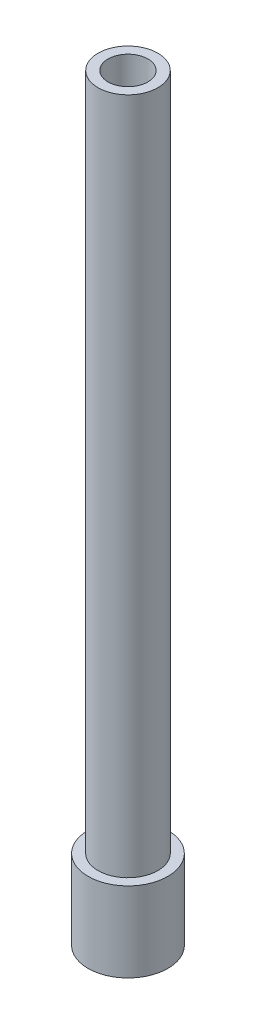
SolidWorks part; units mm, degrees
material "Copper"
ref_plane "Front Plane" through (0, 0, 0) normal (0, 0, 1) x (1, 0, 0)
ref_plane "Top Plane" through (0, 0, 0) normal (0, 1, 0) x (1, 0, 0)
ref_plane "Right Plane" through (0, 0, 0) normal (1, 0, 0) x (0, 0, -1)
sketch "Sketch1" plane through (0, 0, 0) normal (0, 1, 0) x (1, 0, 0)
  circle A0 centre (0, 0) radius 3.175
  dimension "D1" = 6.35
extrude "Boss-Extrude1" add sketch "Sketch1" along normal blind 6.35
sketch "Sketch4" plane through (0, 6.35, 0) normal (0, 1, 0) x (1, 0, 0)
  circle A0 centre (0, 0) radius 2.3813
  dimension "D1" = 4.7625
extrude "Boss-Extrude3" add sketch "Sketch4" along normal blind 53.975
sketch "Sketch5" plane through (0, 60.325, 0) normal (0, 1, 0) x (1, 0, 0)
  circle A0 centre (0, 0) radius 1.5875
  dimension "D1" = 3.175
extrude "Cut-Extrude1" cut sketch "Sketch5" against normal through all
